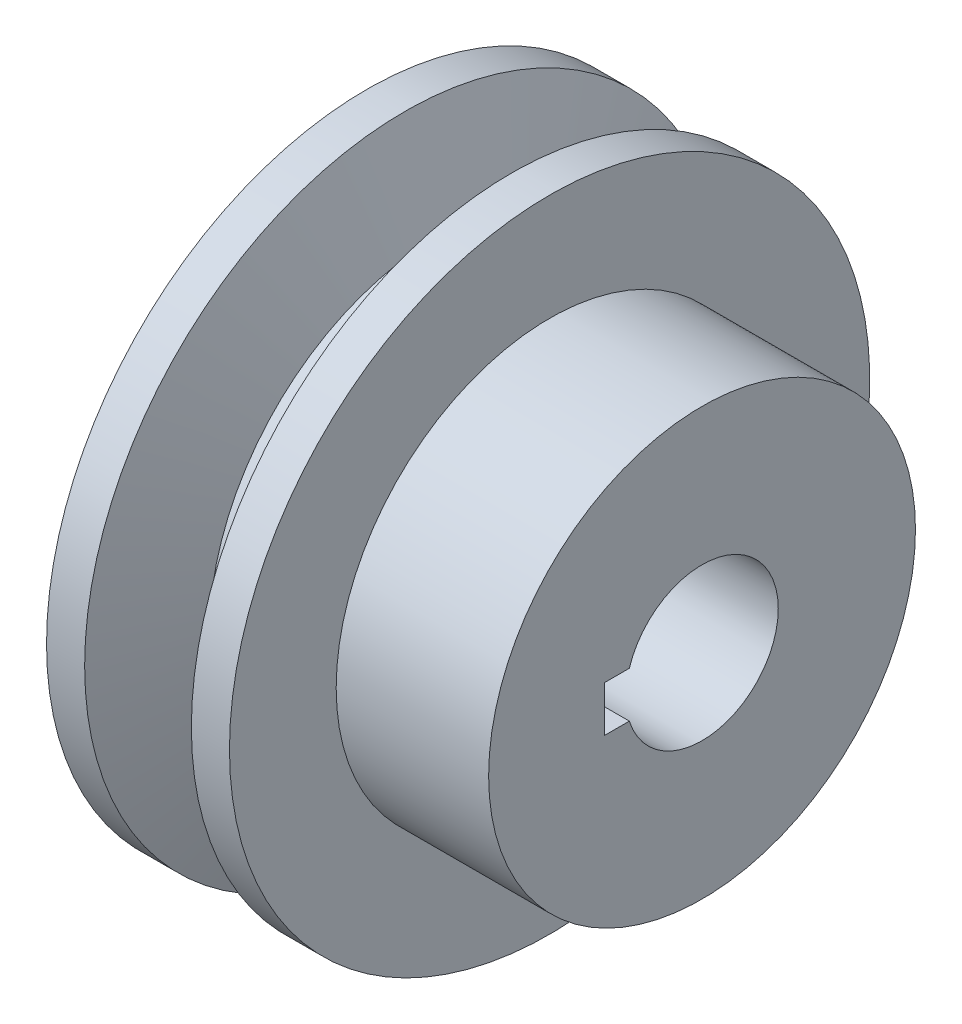
SolidWorks part; units mm, degrees
ref_plane "Front Plane" through (0, 0, 0) normal (0, 0, 1) x (1, 0, 0)
ref_plane "Top Plane" through (0, 0, 0) normal (0, 1, 0) x (1, 0, 0)
ref_plane "Right Plane" through (0, 0, 0) normal (1, 0, 0) x (0, 0, -1)
sketch "Sketch1" plane through (0, 0, 0) normal (0, 0, 1) x (1, 0, 0)
  line L0 (0, 0) -> (22, 0)
  line L1 (0, 0) -> (0, 21)
  line L2 (0, 21) -> (2.5, 21)
  line L3 (2.5, 21) -> (4.6838, 15)
  line L4 (4.6838, 15) -> (7.3162, 15)
  line L5 (7.3162, 15) -> (9.5, 21)
  line L6 (9.5, 21) -> (12, 21)
  line L7 (12, 21) -> (12, 14)
  line L9 (12, 14) -> (22, 14)
  line L10 (22, 14) -> (22, 0)
  dimension "D1" = 22
  dimension "D2" = 40
  dimension "D3" = 21
  dimension "D4" = 21
  dimension "D5" = 7
  dimension "D6" = 2.5
  dimension "D7" = 2.5
  dimension "D8" = 14
  dimension "D9" = 15
revolve "Revolve1" add sketch "Sketch1" angle 360 about L0
sketch "Sketch2" plane through (0, 0, 0) normal (-1, 0, 0) x (0, 0, 1)
  line L1 (4.7697, 1.5) -> (6.4, 1.5)
  line L2 (6.4, 1.5) -> (6.4, -1.5)
  line L3 (6.4, -1.5) -> (4.7697, -1.5)
  arc A0 (4.7697, 1.5) -> (4.7697, -1.5) centre (0, 0) ccw
  dimension "D1" = 10
  dimension "D2" = 6.4
extrude "Cut-Extrude1" cut sketch "Sketch2" against normal through all
